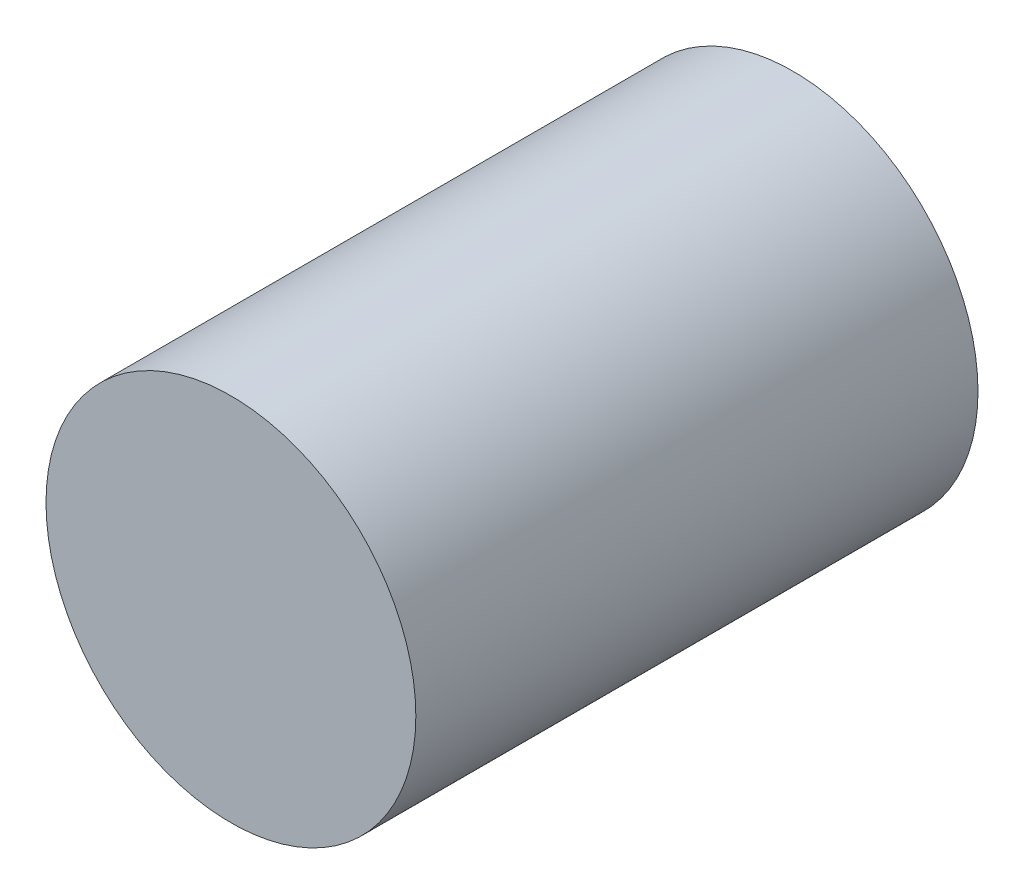
SolidWorks part; units mm, degrees
ref_plane "Front Plane" through (0, 0, 0) normal (0, 0, 1) x (1, 0, 0)
ref_plane "Top Plane" through (0, 0, 0) normal (0, 1, 0) x (1, 0, 0)
ref_plane "Right Plane" through (0, 0, 0) normal (1, 0, 0) x (0, 0, -1)
sketch "Sketch1" plane through (0, 0, 0) normal (0, 0, 1) x (1, 0, 0)
  circle A1 centre (-0.4057, -16.3824) radius 0.25
extrude "Boss-Extrude1" add sketch "Sketch1" along normal blind 0.76
